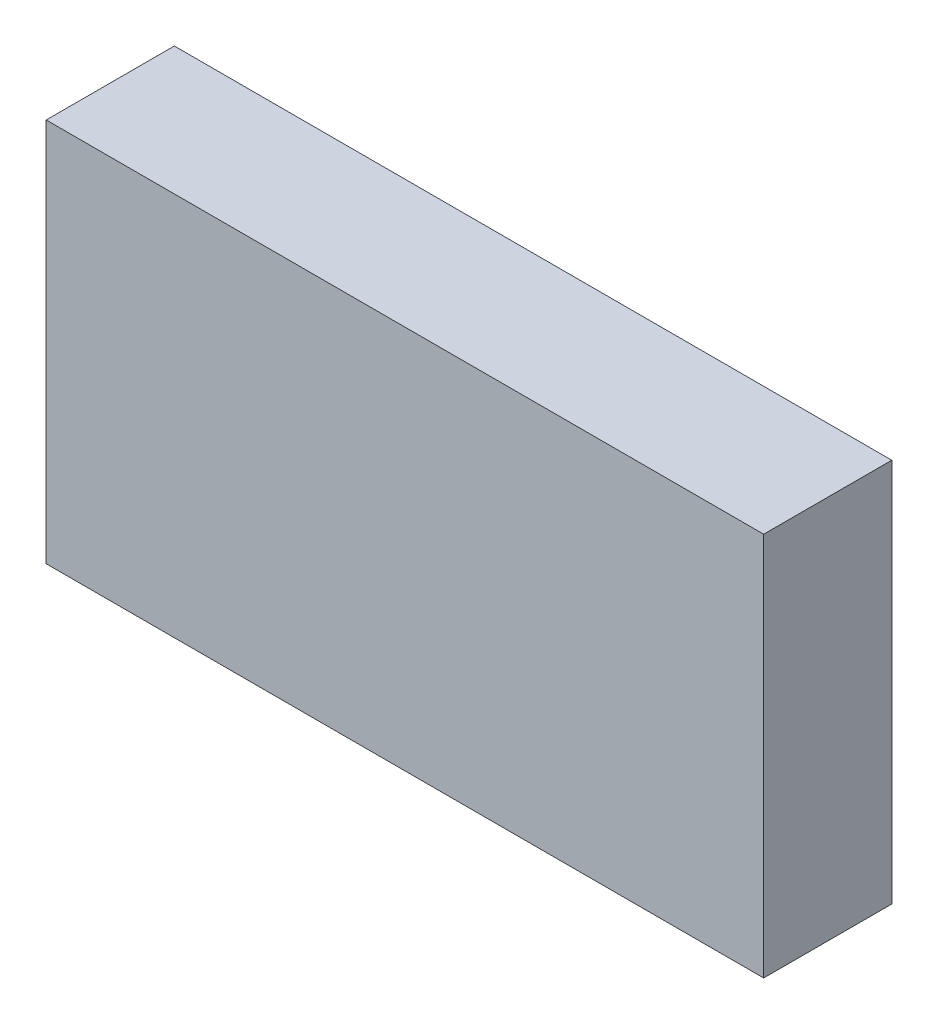
SolidWorks part; units mm, degrees
ref_plane "Plan de face" through (0, 0, 0) normal (0, 0, 1) x (1, 0, 0)
ref_plane "Plan de dessus" through (0, 0, 0) normal (0, 1, 0) x (1, 0, 0)
ref_plane "Plan de droite" through (0, 0, 0) normal (1, 0, 0) x (0, 0, -1)
sketch "Esquisse1" plane through (0, 0, 0) normal (0, 0, 1) x (1, 0, 0)
  line L1 (-28.7082, 15.5294) -> (27.2918, 15.5294)
  line L2 (-28.7082, 15.5294) -> (-28.7082, -14.4706)
  line L3 (-28.7082, -14.4706) -> (27.2918, -14.4706)
  line L4 (27.2918, 15.5294) -> (27.2918, -14.4706)
  dimension "D1" = 30
  dimension "D2" = 56
extrude "Boss.-Extru.1" add sketch "Esquisse1" along normal blind 10
